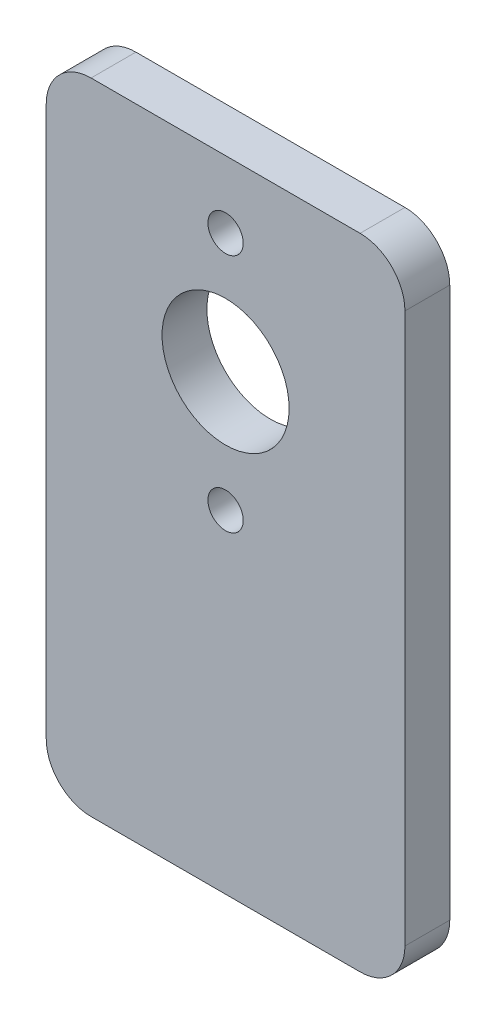
SolidWorks part; units mm, degrees
material "6061 Alloy"
ref_plane "Front Plane" through (0, 0, 0) normal (0, 0, 1) x (1, 0, 0)
ref_plane "Top Plane" through (0, 0, 0) normal (0, 1, 0) x (1, 0, 0)
ref_plane "Right Plane" through (0, 0, 0) normal (1, 0, 0) x (0, 0, -1)
sketch "Sketch1" plane through (0, 0, 0) normal (0, 0, 1) x (1, 0, 0)
  line L1 (-12.7, -22.6475) -> (12.7, -22.6475)
  line L2 (-12.7, -22.6475) -> (-12.7, 22.6475)
  line L3 (-12.7, 22.6475) -> (12.7, 22.6475)
  line L4 (12.7, -22.6475) -> (12.7, 22.6475)
  line L5 (-12.7, -22.6475) -> (12.7, 22.6475) construction
  line L6 (-12.7, 22.6475) -> (12.7, -22.6475) construction
  point P0 (0, 0)
  dimension "D1" = 25.4
  dimension "D2" = 45.295
extrude "Boss-Extrude1" add sketch "Sketch1" along normal blind 3.175
sketch "Sketch2" plane through (0, 0, 3.175) normal (0, 0, 1) x (1, 0, 0)
  line L0 (12.7, -22.6475) -> (12.7, 22.6475) construction
  line L1 (12.7, 22.6475) -> (-12.7, 22.6475) construction
  circle A0 centre (0, 9.3975) radius 4.5
  dimension "D1" = 9
  dimension "D2" = 12.7
  dimension "D3" = 13.25
extrude "Cut-Extrude1" cut sketch "Sketch2" against normal through all
ref_plane "Plane1" through (0, 0, 3.175) normal (0, 0, 1) x (1, 0, 0)
sketch "Sketch3" plane through (0, 0, 3.175) normal (0, 0, 1) x (1, 0, 0)
  line L1 (-12.7, 22.6475) -> (-12.7, -22.6475) construction
  line L2 (12.7, 22.6475) -> (-12.7, 22.6475) construction
  point P0 (0, 17.8975)
  point P1 (0, 0.8975)
  dimension "D1" = 17
  dimension "D2" = 12.7
  dimension "D3" = 4.75
hole_wizard "M3x0.5 Tapped Hole1" positions "Sketch4" profile "Sketch5" tap size "M3x0.5" standard "ANSI Metric" end condition through all
sketch "Sketch4" plane through (0, 0, 3.175) normal (0, 0, 1) x (1, 0, 0)
  point P0 (0, 17.8975)
  point P3 (0, 0.8975)
sketch "Sketch5" plane through (0, 17.8975, 3.175) normal (1, 0, 0) x (0, -1, 0)
  line L0 (0, 0) -> (0, 3.175)
  line L1 (0, 3.175) -> (1.25, 3.175)
  line L2 (1.25, 3.175) -> (1.25, 0)
  line L5 (1.25, 0) -> (0, 0)
  line L11 (0, -6.35) -> (0, 107.95) construction
  dimension "Thru Tap Drill Dia." = 2.5
  dimension "Thru Tap Drill Depth" = 3.175
fillet "Fillet1" radius 3.175 4 edges at (-12.7, -22.6475, 1.5875) (12.7, -22.6475, 1.5875) (12.7, 22.6475, 1.5875) (-12.7, 22.6475, 1.5875)
ref_plane "Plane2" through (0, 0, 3.175) normal (0, 0, 1) x (1, 0, 0)
sketch "Sketch6" [suppressed] plane through (0, 0, 3.175) normal (0, 0, 1) x (1, 0, 0)
  line L0 (-12.7, 19.4725) -> (-12.7, -19.4725) construction
  line L1 (-9.525, -22.6475) -> (9.525, -22.6475) construction
  point P0 (-6.35, -15.1475)
  point P1 (6.35, -15.1475)
  dimension "D1" = 12.7
  dimension "D2" = 6.35
  dimension "D3" = 7.5
hole_wizard "M4x0.7 Tapped Hole1" [suppressed] positions "Sketch7" profile "Sketch8" tap size "M4x0.7" standard "ANSI Metric"
sketch "Sketch7" [suppressed] plane through (0, 0, 3.175) normal (0, 0, 1) x (1, 0, 0)
  point P0 (-6.35, -15.1475)
  point P3 (6.35, -15.1475)
sketch "Sketch8" plane through (-6.35, -15.1475, 3.175) normal (1, 0, 0) x (0, -1, 0)
  line L0 (0, 0) -> (0, 3.175)
  line L1 (0, 3.175) -> (1.65, 3.175)
  line L2 (1.65, 3.175) -> (1.65, 0)
  line L5 (1.65, 0) -> (0, 0)
  line L11 (0, -6.35) -> (0, 107.95) construction
  dimension "Thru Tap Drill Dia." = 3.3
  dimension "Thru Tap Drill Depth" = 3.175
